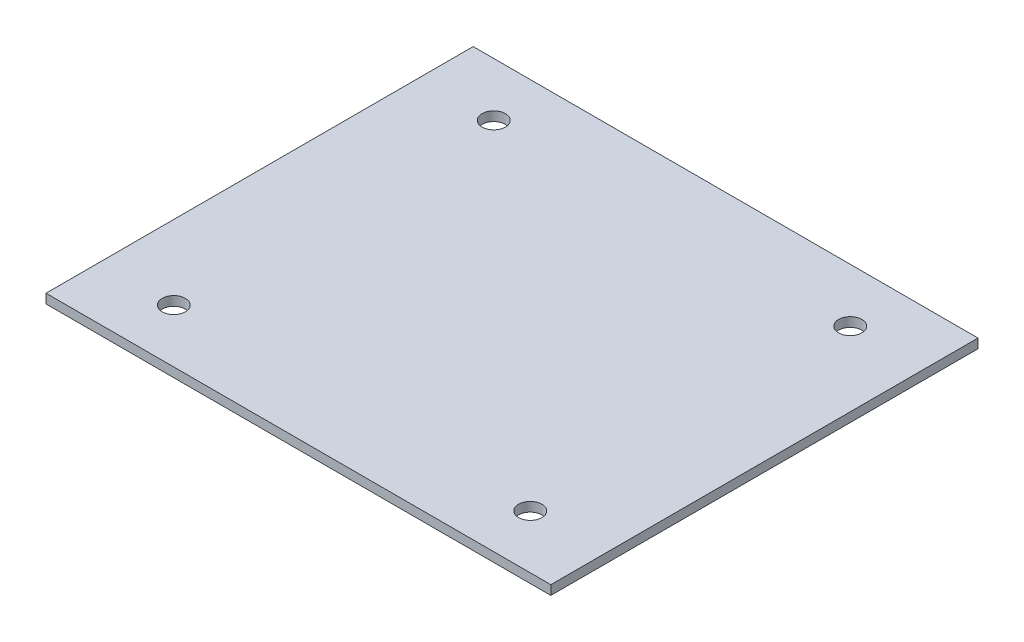
SolidWorks part; units mm, degrees
ref_plane "前视基准面" through (0, 0, 0) normal (0, 0, 1) x (1, 0, 0)
ref_plane "上视基准面" through (0, 0, 0) normal (0, 1, 0) x (1, 0, 0)
ref_plane "右视基准面" through (0, 0, 0) normal (1, 0, 0) x (0, 0, -1)
sketch "草图2" plane through (0, 0, 0) normal (0, 1, 0) x (1, 0, 0)
  line L0 (-39.4186, 0) -> (42.1357, 0) construction
  line L1 (0, 38.4918) -> (0, -38.6805) construction
  line L2 (-32.5, 27.5) -> (-32.5, -27.5)
  line L3 (-32.5, -27.5) -> (32.5, -27.5)
  line L4 (32.5, -27.5) -> (32.5, 27.5)
  line L5 (32.5, 27.5) -> (-32.5, 27.5)
  circle A0 centre (-22.95, 20.6) radius 1.5
  circle A1 centre (-22.95, -20.6) radius 1.5
  circle A2 centre (22.95, -20.6) radius 1.5
  circle A3 centre (22.95, 20.6) radius 1.5
  dimension "D3" = 3
  dimension "D4" = 45.9
  dimension "D1" = 65
  dimension "D2" = 55
  dimension "D5" = 41.2
extrude "凸台-拉伸2" add sketch "草图2" along normal blind 1.2
